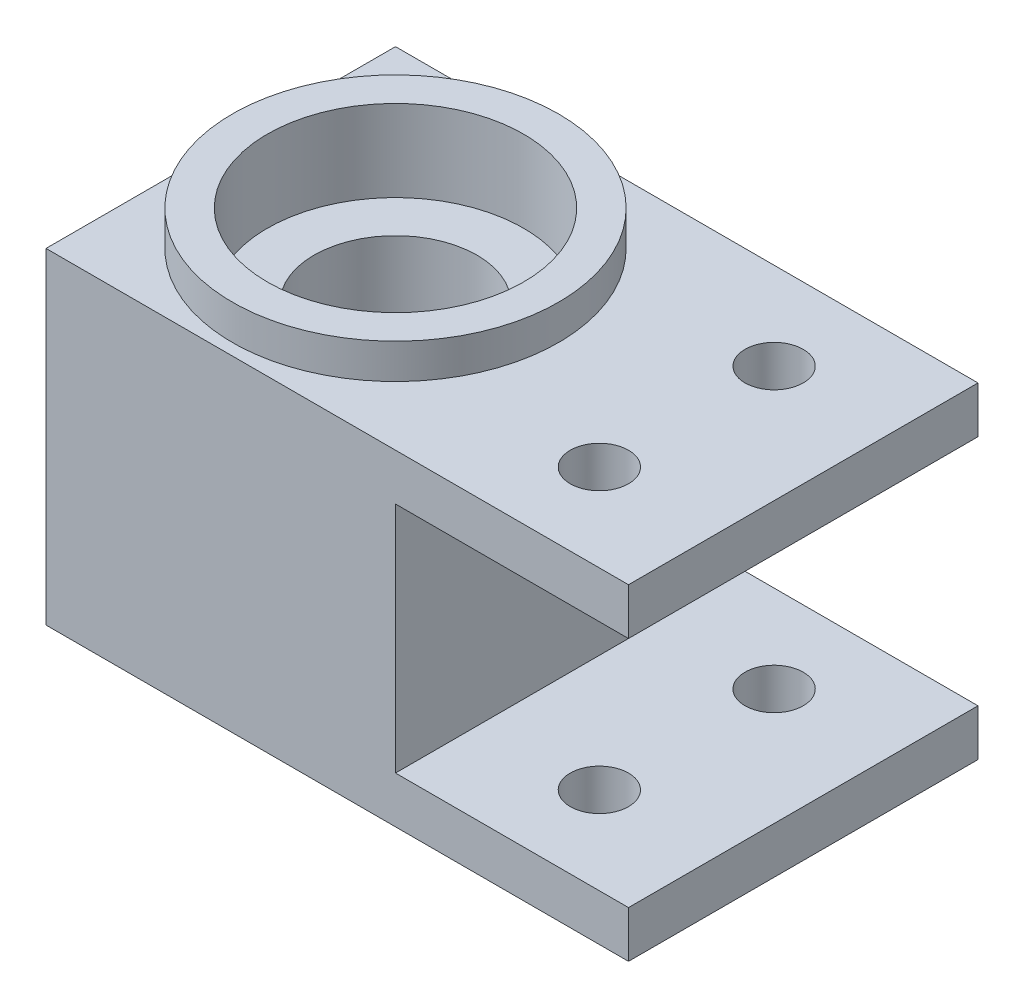
SolidWorks part; units mm, degrees
ref_plane "Front Plane" through (0, 0, 0) normal (0, 0, 1) x (1, 0, 0)
ref_plane "Top Plane" through (0, 0, 0) normal (0, 1, 0) x (1, 0, 0)
ref_plane "Right Plane" through (0, 0, 0) normal (1, 0, 0) x (0, 0, -1)
ref_plane "Plane1" through (0, 14, 0) normal (0, 1, 0) x (1, 0, 0)
sketch "Sketch1" plane through (0, 14, 0) normal (0, 1, 0) x (1, 0, 0)
  line L0 (10, 0) -> (-40, 0)
  line L1 (-40, 0) -> (-40, -30)
  line L2 (-40, -30) -> (10, -30)
  line L3 (10, -30) -> (10, 0)
extrude "Boss-Extrude1" add sketch "Sketch1" against normal blind 28
sketch "Sketch2" plane through (0, 0, 0) normal (0, 0, -1) x (-1, 0, 0)
  line L0 (-10, 10) -> (-10, -10)
  line L1 (-10, -10) -> (10, -10)
  line L2 (10, -10) -> (10, 10)
  line L3 (10, 10) -> (-10, 10)
extrude "Cut-Extrude1" cut sketch "Sketch2" against normal through all
ref_plane "Plane2" through (0, 0, 15) normal (0, 0, 1) x (1, 0, 0)
sketch "Sketch3" plane through (0, 0, 15) normal (0, 0, 1) x (1, 0, 0)
  line L0 (-11, 17) -> (-25, 17)
  line L1 (-25, 17) -> (-25, 14)
  line L2 (-25, 14) -> (-11, 14)
  line L3 (-11, 14) -> (-11, 17)
  line L4 (-25, 17) -> (-25, 14) construction
revolve "Revolve1" add sketch "Sketch3" angle 360 about L4
ref_plane "Plane3" through (0, 0, 15) normal (0, 0, -1) x (-1, 0, 0)
sketch "Sketch4" plane through (0, 0, 15) normal (0, 0, -1) x (-1, 0, 0)
  line L0 (14, -14) -> (25, -14)
  line L1 (25, -14) -> (25, 17)
  line L2 (25, 17) -> (14, 17)
  line L3 (14, 17) -> (14, 10)
  line L4 (14, 10) -> (18, 10)
  line L5 (18, 10) -> (18, -7)
  line L6 (18, -7) -> (14, -7)
  line L7 (14, -7) -> (14, -14)
  line L8 (25, -14) -> (25, 17) construction
revolve "Cut-Revolve1" cut sketch "Sketch4" angle 360 about L8
hole_wizard "Ø5.0 (5) Diameter Hole1" positions "Sketch6" profile "Sketch5" hole size "Ø5.0" standard "ANSI Metric"
sketch "Sketch6" plane through (0, 10, 0) normal (0, -1, 0) x (-1, 0, 0)
  point P0 (0, -7.5)
  point P1 (0, -22.5)
sketch "Sketch5" plane through (0, 10, 7.5) normal (1, 0, 0) x (0, 0, -1)
  line L0 (0, 0) -> (0, 7)
  line L1 (0, 7) -> (2.5, 7)
  line L2 (2.5, 7) -> (2.5, 0)
  line L5 (2.5, 0) -> (0, 0)
  line L11 (0, -6.35) -> (0, 107.95) construction
  dimension "Thru Hole Dia." = 5
  dimension "Thru Hole Depth" = 7
hole_wizard "Ø5.0 (5) Diameter Hole2" positions "Sketch8" profile "Sketch7" hole size "Ø5.0" standard "ANSI Metric"
sketch "Sketch8" plane through (0, -14, 0) normal (0, -1, 0) x (-1, 0, 0)
  point P0 (0, -7.5)
  point P1 (0, -22.5)
sketch "Sketch7" plane through (0, -14, 7.5) normal (1, 0, 0) x (0, 0, -1)
  line L0 (0, 0) -> (0, 31)
  line L1 (0, 31) -> (2.5, 31)
  line L2 (2.5, 31) -> (2.5, 0)
  line L5 (2.5, 0) -> (0, 0)
  line L11 (0, -6.35) -> (0, 107.95) construction
  dimension "Thru Hole Dia." = 5
  dimension "Thru Hole Depth" = 31
